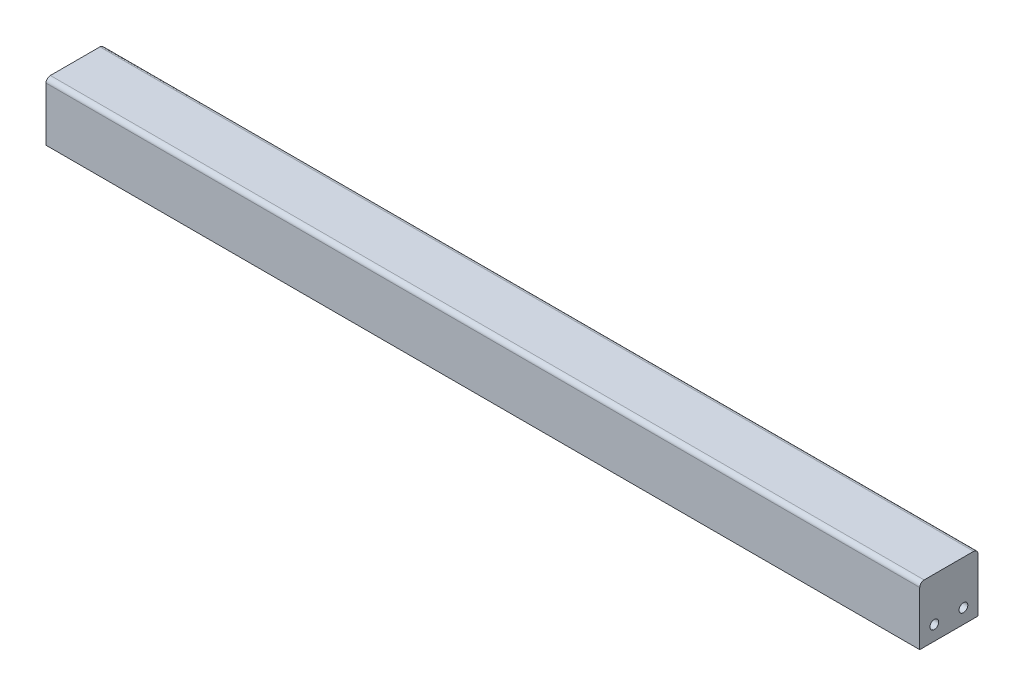
SolidWorks part; units mm, degrees
material "Aleación 1060"
ref_plane "Alzado" through (0, 0, 0) normal (0, 0, 1) x (1, 0, 0)
ref_plane "Planta" through (0, 0, 0) normal (0, 1, 0) x (1, 0, 0)
ref_plane "Vista lateral" through (0, 0, 0) normal (1, 0, 0) x (0, 0, -1)
sketch "Croquis1" plane through (0, 0, 0) normal (1, 0, 0) x (0, 0, -1)
  line L0 (-20, -10) -> (20, -10) construction
  line L1 (20, -20) -> (-20, -20)
  line L2 (20, -20) -> (20, 17)
  line L3 (17, 20) -> (-17, 20)
  line L4 (-20, -20) -> (-20, 17)
  line L5 (20, -20) -> (-20, 20) construction
  line L6 (20, 20) -> (-20, -20) construction
  arc A0 (20, 17) -> (17, 20) centre (17, 17) ccw
  arc A1 (-17, 20) -> (-20, 17) centre (-17, 17) ccw
  point P0 (0, 0)
  dimension "D3" = 3
  dimension "D1" = 40
  dimension "D2" = 40
  dimension "D4" = 10
extrude "Saliente-Extruir1" add sketch "Croquis1" along normal mid plane 600
sketch "Croquis2" plane through (-300, 0, 0) normal (-1, 0, 0) x (0, 0, 1)
  line L1 (20, -20) -> (-20, -20) construction
  line L3 (-20, -20) -> (-20, 17) construction
  circle A0 centre (-10, -10) radius 3
  circle A1 centre (10, -10) radius 3
  point P4 (0, 0)
  point P9 (-20, -3.0569)
  dimension "D1" = 20
  dimension "D2" = 10
  dimension "D3" = 10
extrude "Cortar-Extruir1" cut sketch "Croquis2" against normal blind 10
mirror "Simetría1" about plane through (0, 0, 0) normal (1, 0, 0) of "Cortar-Extruir1"
